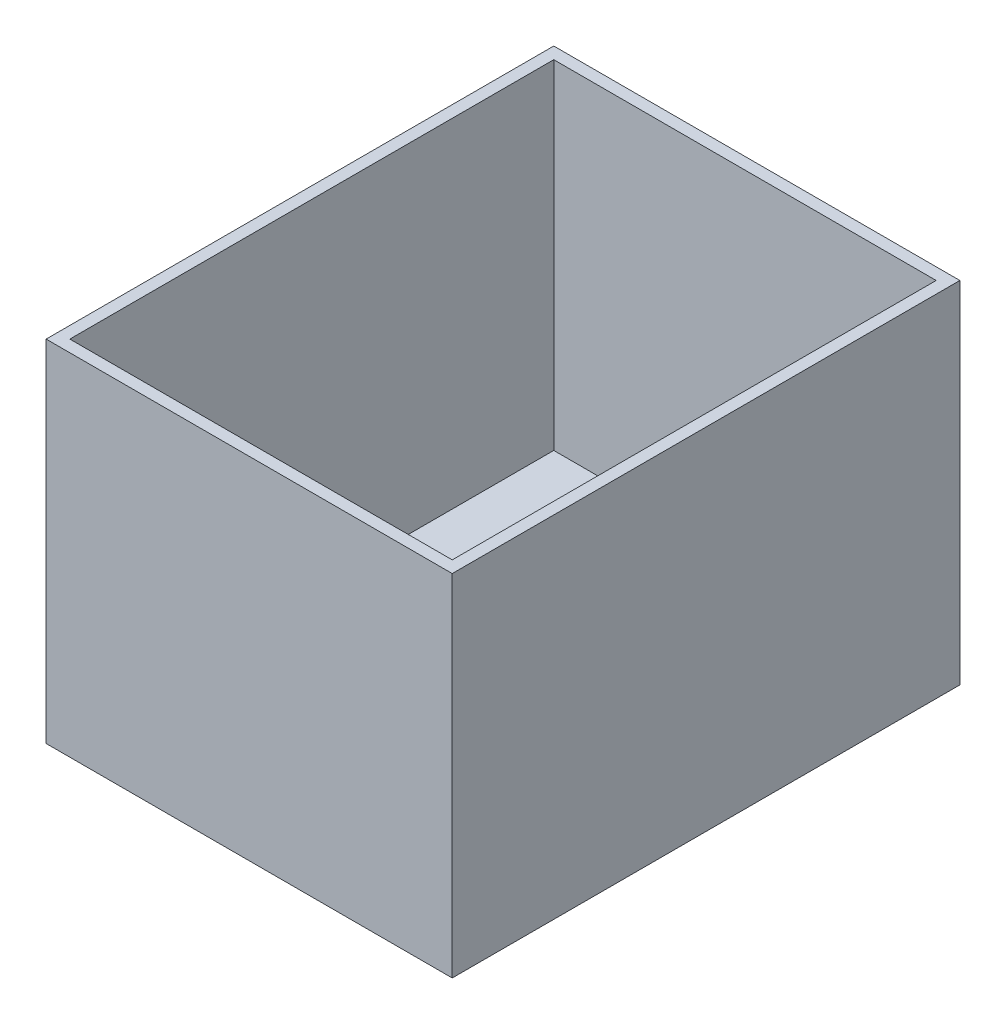
SolidWorks part; units mm, degrees
ref_plane "Front Plane" through (0, 0, 0) normal (0, 0, 1) x (1, 0, 0)
ref_plane "Top Plane" through (0, 0, 0) normal (0, 1, 0) x (1, 0, 0)
ref_plane "Right Plane" through (0, 0, 0) normal (1, 0, 0) x (0, 0, -1)
sketch "Sketch1" plane through (0, 0, 0) normal (0, 1, 0) x (1, 0, 0)
  line L1 (0, 0) -> (-120, 0)
  line L2 (0, 0) -> (0, 150)
  line L3 (0, 150) -> (-120, 150)
  line L4 (-120, 0) -> (-120, 150)
  dimension "D1" = 150
  dimension "D2" = 120
extrude "Boss-Extrude1" add sketch "Sketch1" along normal blind 3.5
sketch "Sketch2" plane through (0, 3.5, 0) normal (0, 1, 0) x (1, 0, 0)
  line L0 (0, 0) -> (0, 150) construction
  line L1 (-3.5, 3.5) -> (-116.5, 3.5)
  line L2 (-3.5, 3.5) -> (-3.5, 146.5)
  line L3 (-3.5, 146.5) -> (-116.5, 146.5)
  line L4 (-116.5, 3.5) -> (-116.5, 146.5)
  line L5 (-120, 0) -> (0, 0) construction
  line L6 (0, 150) -> (-120, 150) construction
  line L7 (-120, 150) -> (-120, 0) construction
  line L12 (0, 0) -> (0, 150)
  line L13 (0, 150) -> (-120, 150)
  line L14 (-120, 150) -> (-120, 0)
  line L15 (-120, 0) -> (0, 0)
  line L16 (0, 0) -> (0, 150)
  line L17 (0, 150) -> (-120, 150)
  line L18 (-120, 150) -> (-120, 0)
  line L19 (-120, 0) -> (0, 0)
  dimension "D1" = 3.5
  dimension "D2" = 3.5
  dimension "D3" = 3.5
  dimension "D4" = 3.5
  dimension "D5" = 0
extrude "Boss-Extrude3" add sketch "Sketch2" along normal blind 100
